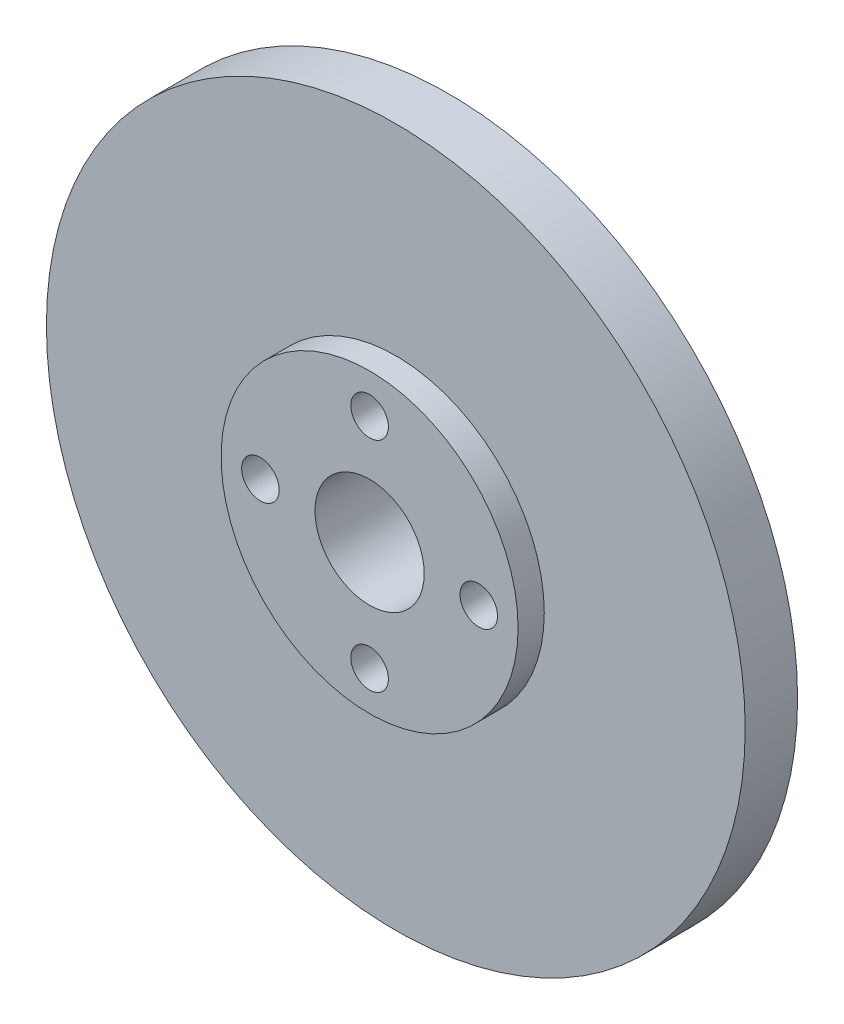
SolidWorks part; units mm, degrees
ref_plane "Front Plane" through (0, 0, 0) normal (0, 0, 1) x (1, 0, 0)
ref_plane "Top Plane" through (0, 0, 0) normal (0, 1, 0) x (1, 0, 0)
ref_plane "Right Plane" through (0, 0, 0) normal (1, 0, 0) x (0, 0, -1)
sketch "Sketch1" plane through (0, 0, 0) normal (0, 0, 1) x (1, 0, 0)
  circle A0 centre (0, 0) radius 40
  dimension "D1" = 80
extrude "Boss-Extrude1" add sketch "Sketch1" along normal blind 6
sketch "Sketch2" plane through (0, 0, 6) normal (0, 0, 1) x (1, 0, 0)
  circle A0 centre (0, 0) radius 17
  dimension "D1" = 34
extrude "Boss-Extrude2" add sketch "Sketch2" along normal blind 3
sketch "Sketch3" plane through (0, 0, 9) normal (0, 0, 1) x (1, 0, 0)
  circle A0 centre (0, 0) radius 6.25
  circle A1 centre (0, 0) radius 12.5 construction
  circle A2 centre (0, 12.5) radius 2.15
  circle A3 centre (12.5, 0) radius 2.15
  circle A4 centre (0, 0) radius 12.5 construction
  circle A5 centre (0, -12.5) radius 2.15
  circle A6 centre (0, 0) radius 12.5 construction
  circle A7 centre (-12.5, 0) radius 2.15
  circle A8 centre (0, 0) radius 12.5 construction
  point P18 (0, 0)
  dimension "D1" = 12.5
  dimension "D2" = 4.3
  dimension "D3" = 25
  dimension "D4" = 4
extrude "Cut-Extrude1" cut sketch "Sketch3" against normal through all both and the other way through all
